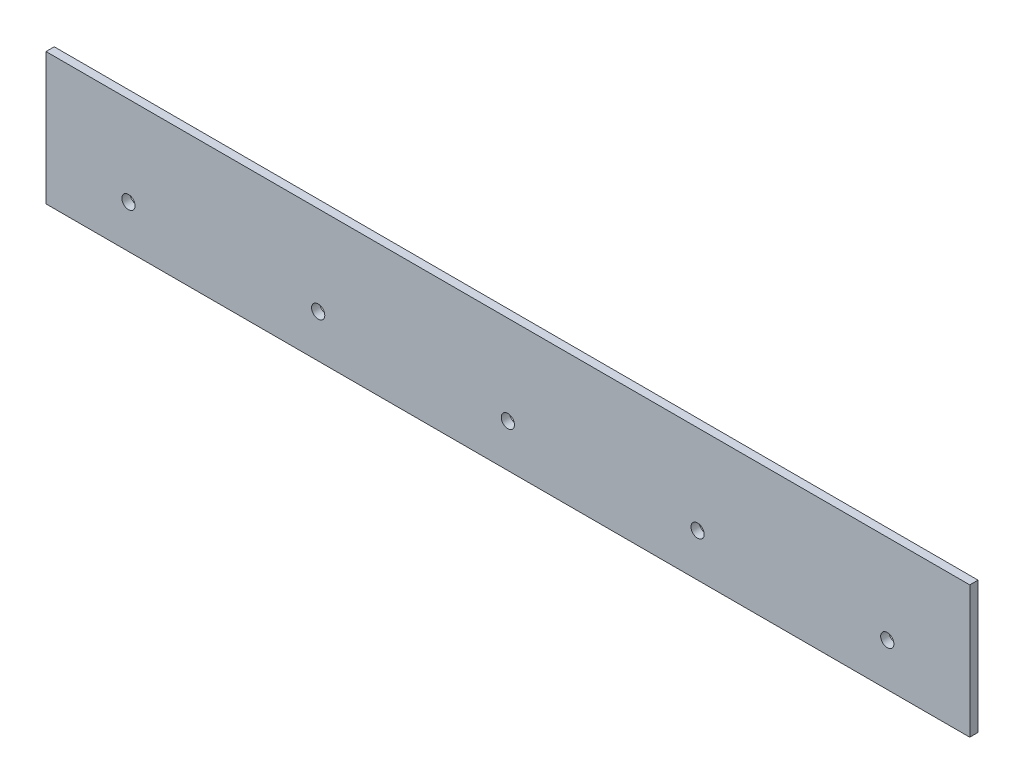
SolidWorks part; units mm, degrees
ref_plane "Front Plane" through (0, 0, 0) normal (0, 0, 1) x (1, 0, 0)
ref_plane "Top Plane" through (0, 0, 0) normal (0, 1, 0) x (1, 0, 0)
ref_plane "Right Plane" through (0, 0, 0) normal (1, 0, 0) x (0, 0, -1)
sketch "Sketch1" plane through (0, 0, 0) normal (0, 0, 1) x (1, 0, 0)
  line L0 (-177.8, 0) -> (177.8, 0) construction
  line L1 (-177.8, -25.4) -> (177.8, -25.4)
  line L2 (-177.8, -25.4) -> (-177.8, 25.4)
  line L3 (-177.8, 25.4) -> (177.8, 25.4)
  line L4 (177.8, -25.4) -> (177.8, 25.4)
  line L5 (0, 25.4) -> (0, -25.4) construction
  line L6 (-146.05, -8.89) -> (0, -8.89) construction
  circle A0 centre (0, -8.89) radius 2.54
  circle A1 centre (-146.05, -8.89) radius 2.54
  circle A2 centre (-73.025, -8.89) radius 2.54
  circle A3 centre (73.025, -8.89) radius 2.54
  circle A4 centre (146.05, -8.89) radius 2.54
  dimension "D5" = 5.08
  dimension "D1" = 50.8
  dimension "D2" = 355.6
  dimension "D4" = 16.51
  dimension "D6" = 292.1
extrude "Boss-Extrude1" add sketch "Sketch1" along normal blind 3.175
sketch "Sketch2" [suppressed] plane through (0, 0, 3.175) normal (0, 0, 1) x (1, 0, 0)
  circle A0 centre (0, -8.89) radius 12.7
  dimension "D1" = 25.4
extrude "Cut-Extrude1" [suppressed] cut sketch "Sketch2" against normal through all
